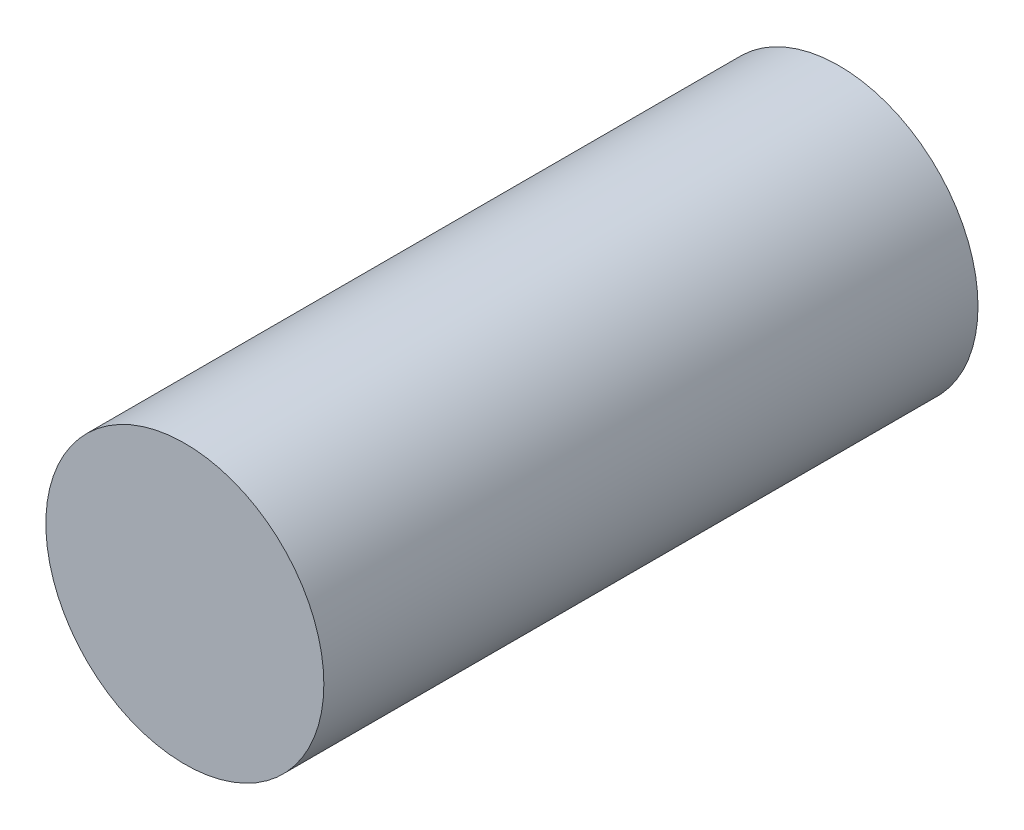
SolidWorks part; units mm, degrees
ref_plane "Front Plane" through (0, 0, 0) normal (0, 0, 1) x (1, 0, 0)
ref_plane "Top Plane" through (0, 0, 0) normal (0, 1, 0) x (1, 0, 0)
ref_plane "Right Plane" through (0, 0, 0) normal (1, 0, 0) x (0, 0, -1)
sketch "Sketch1" plane through (0, 0, 0) normal (0, 0, 1) x (1, 0, 0)
  circle A0 centre (0, 0) radius 17
  dimension "D1" = 34
extrude "Boss-Extrude1" add sketch "Sketch1" along normal mid plane 80
sketch "Sketch2" plane through (0, 0, 0) normal (0, 0, 1) x (1, 0, 0)
  line L0 (0, 0) -> (0, -19.7436) construction
  line L2 (-5, -16) -> (5, -16)
  line L3 (-5, -16) -> (-5, -18)
  line L4 (-5, -18) -> (5, -18)
  line L5 (5, -16) -> (5, -18)
  line L6 (-5, -16) -> (5, -18) construction
  line L7 (-5, -18) -> (5, -16) construction
  circle A0 centre (0, 0) radius 17 construction
  point P3 (0, -17)
  dimension "D1" = 10
  dimension "D2" = 2
extrude "Boss-Extrude2" add sketch "Sketch2" along normal mid plane 10
sketch "Sketch3" plane through (0, -18, 0) normal (0, -1, 0) x (1, 0, 0)
  circle A0 centre (0, 0) radius 2.5
  dimension "D1" = 5
extrude "Cut-Extrude1" cut sketch "Sketch3" against normal blind 10
